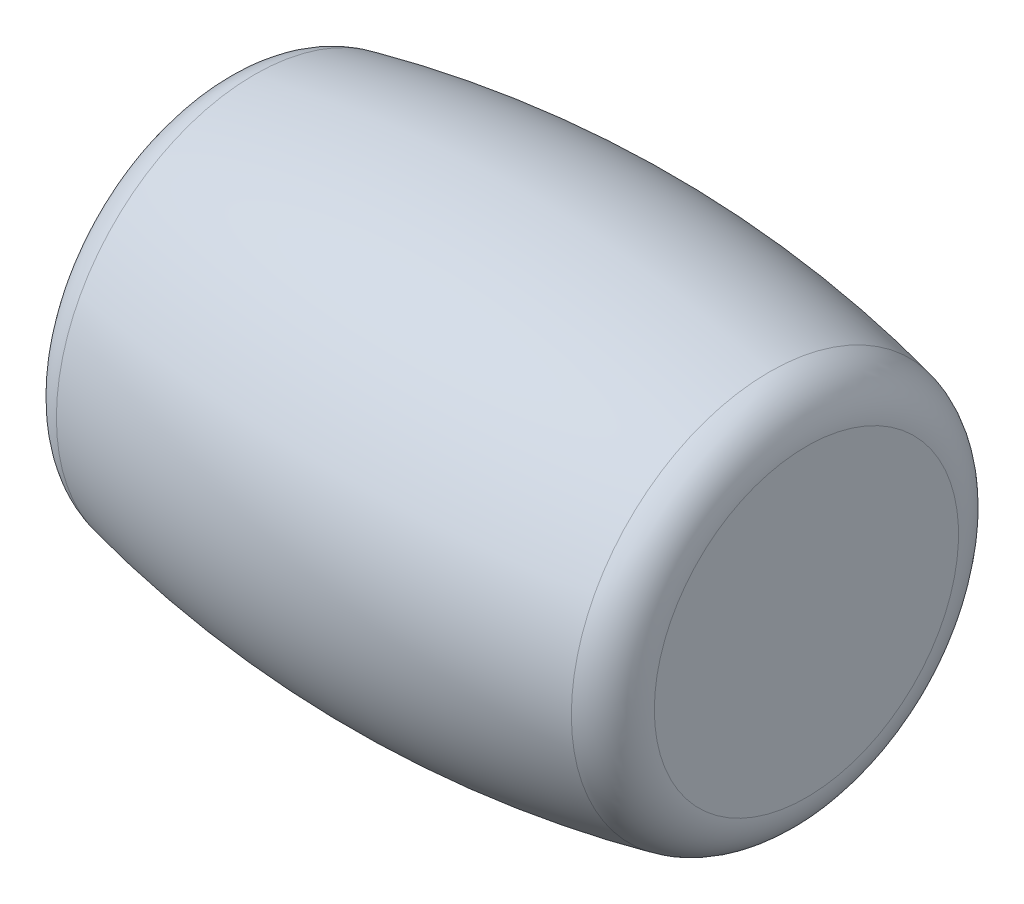
SolidWorks part; units mm, degrees
material "ABS"
ref_plane "Front Plane" through (0, 0, 0) normal (0, 0, 1) x (1, 0, 0)
ref_plane "Top Plane" through (0, 0, 0) normal (0, 1, 0) x (1, 0, 0)
ref_plane "Right Plane" through (0, 0, 0) normal (1, 0, 0) x (0, 0, -1)
sketch "Sketch1" plane through (0, 0, 0) normal (0, 0, 1) x (1, 0, 0)
  line L0 (0, 0) -> (0, 25.4) construction
  line L1 (0, 25.4) -> (0, 61.2801) construction
  line L2 (-6.25, 23.8285) -> (-6.25, 20.6)
  line L3 (6.25, 23.8285) -> (6.25, 20.6)
  line L4 (-6.25, 20.6) -> (6.25, 20.6)
  arc A0 (-5.4652, 24.8051) -> (5.4652, 24.8051) centre (0, 0) cw
  arc A1 (-5.4652, 24.8051) -> (-6.25, 23.8285) centre (-5.25, 23.8285) ccw
  arc A2 (5.4652, 24.8051) -> (6.25, 23.8285) centre (5.25, 23.8285) cw
  dimension "D1" = 25.4
  dimension "D4" = 1
  dimension "D5" = 1
  dimension "D2" = 4.8
  dimension "D3" = 12.5
revolve "Revolve1" add sketch "Sketch1" angle 360 about L4
